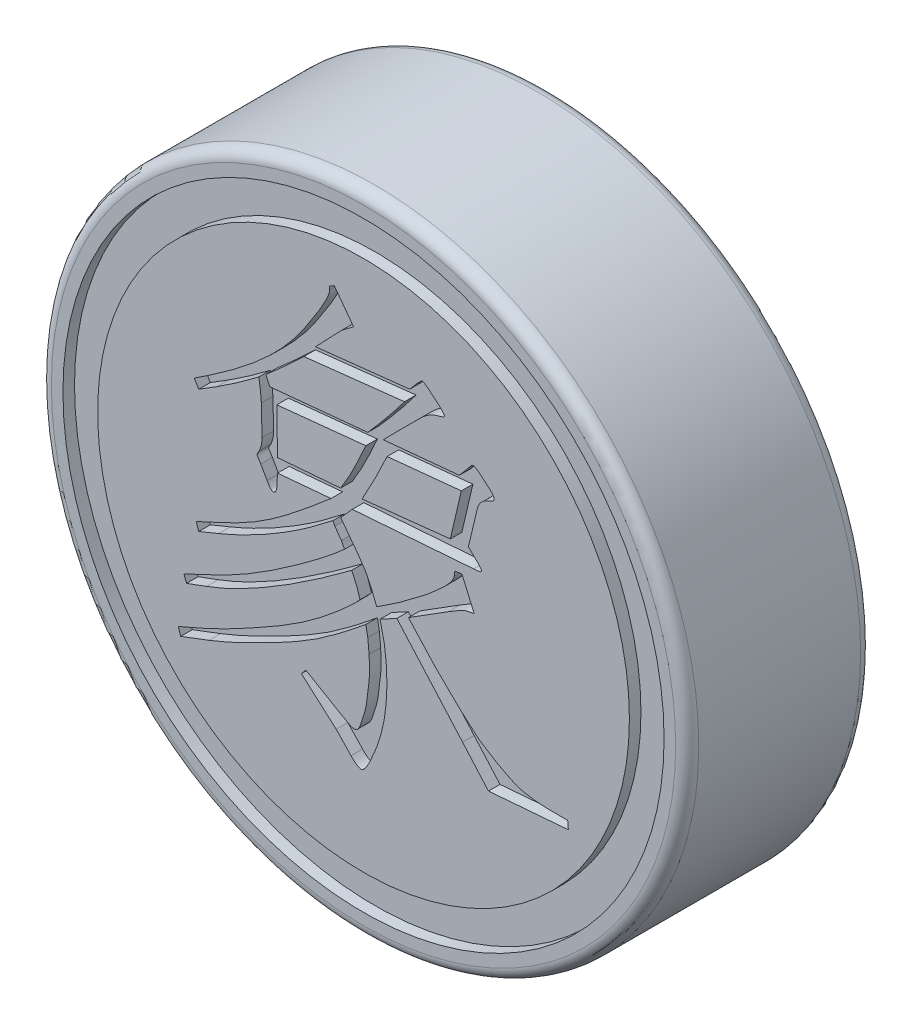
SolidWorks part; units mm, degrees
ref_plane "前视基准面" through (0, 0, 0) normal (0, 0, 1) x (1, 0, 0)
ref_plane "上视基准面" through (0, 0, 0) normal (0, 1, 0) x (1, 0, 0)
ref_plane "右视基准面" through (0, 0, 0) normal (1, 0, 0) x (0, 0, -1)
sketch "草图1" plane through (0, 0, 0) normal (0, 0, 1) x (1, 0, 0)
  circle A0 centre (0, 0) radius 14
extrude "凸台-拉伸1" add sketch "草图1" along normal blind 8
sketch "草图2" plane through (0, 0, 8) normal (0, 0, 1) x (1, 0, 0)
  circle A0 centre (0, 0) radius 13
  circle A1 centre (0, 0) radius 11.5
extrude "切除-拉伸1" cut sketch "草图2" against normal blind 0.5
sketch "草图3" plane through (0, 0, 0) normal (0, 0, -1) x (-1, 0, 0)
  circle A0 centre (0, 0) radius 5.1
extrude "切除-拉伸2" cut sketch "草图3" against normal blind 5
chamfer "倒角1" distance 0.5 angle 45 1 edges at (-5.1, 0, 0)
fillet "圆角1" radius 0.5 2 edges at (14, 0, 8) (14, 0, 0)
sketch "草图4" plane through (0, 0, 8) normal (0, 0, 1) x (1, 0, 0)
  text T0 "象" font "汉仪长仿宋体" height 13
extrude "切除-拉伸3" cut sketch "草图4" against normal blind 0.5
